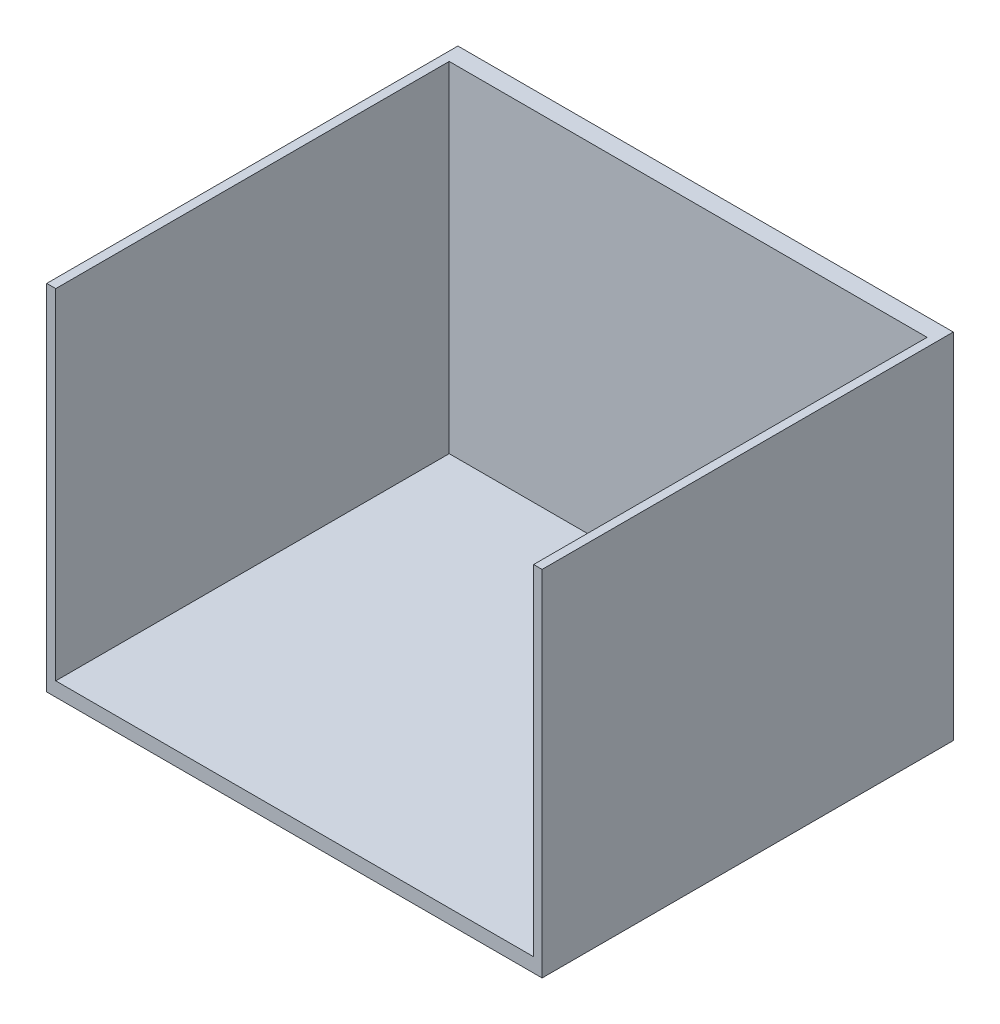
SolidWorks part; units mm, degrees
ref_plane "Front Plane" through (0, 0, 0) normal (0, 0, 1) x (1, 0, 0)
ref_plane "Top Plane" through (0, 0, 0) normal (0, 1, 0) x (1, 0, 0)
ref_plane "Right Plane" through (0, 0, 0) normal (1, 0, 0) x (0, 0, -1)
sketch "Sketch1" plane through (0, 0, 0) normal (0, 0, 1) x (1, 0, 0)
  line L1 (-32.6946, 16.7147) -> (56.2054, 16.7147)
  line L2 (-32.6946, 16.7147) -> (-32.6946, -46.7853)
  line L3 (-32.6946, -46.7853) -> (56.2054, -46.7853)
  line L4 (56.2054, 16.7147) -> (56.2054, -46.7853)
  dimension "D1" = 88.9
  dimension "D2" = 63.5
extrude "Boss-Extrude1" add sketch "Sketch1" along normal blind 3.175
sketch "Sketch4" plane through (0, 0, 3.175) normal (0, 0, 1) x (1, 0, 0)
  line L0 (-32.6946, -46.7853) -> (56.2054, -46.7853) construction
  line L1 (-32.6946, 16.7147) -> (-31.0769, 16.7147)
  line L2 (-32.6946, 16.7147) -> (-32.6946, -46.7853)
  line L3 (-32.6946, -46.7853) -> (-31.0769, -46.7853)
  line L4 (-31.0769, 16.7147) -> (-31.0769, -46.7853)
extrude "Boss-Extrude2" add sketch "Sketch4" along normal blind 70.612
sketch "Sketch5" plane through (0, 0, 3.175) normal (0, 0, 1) x (1, 0, 0)
  line L0 (-31.0769, -46.7853) -> (56.2054, -46.7853) construction
  line L1 (56.2054, 16.7147) -> (54.6814, 16.7147)
  line L2 (56.2054, 16.7147) -> (56.2054, -46.7853)
  line L3 (56.2054, -46.7853) -> (54.6814, -46.7853)
  line L4 (54.6814, 16.7147) -> (54.6814, -46.7853)
  dimension "D1" = 1.524
extrude "Boss-Extrude3" add sketch "Sketch5" along normal blind 70.612
sketch "Sketch6" plane through (0, -46.7853, 0) normal (0, -1, 0) x (1, 0, 0)
  line L1 (-32.6946, 0) -> (56.2054, 0)
  line L2 (-32.6946, 0) -> (-32.6946, 73.787)
  line L3 (-32.6946, 73.787) -> (56.2054, 73.787)
  line L4 (56.2054, 0) -> (56.2054, 73.787)
extrude "Boss-Extrude4" add sketch "Sketch6" against normal blind 2.54
